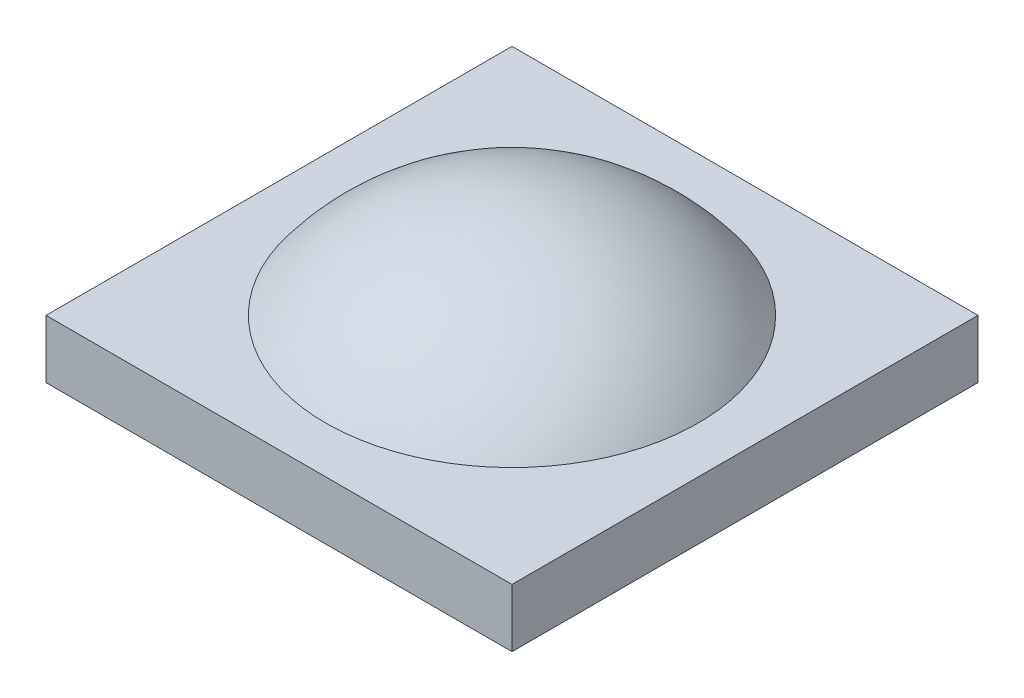
SolidWorks part; units mm, degrees
ref_plane "Front Plane" through (0, 0, 0) normal (0, 0, 1) x (1, 0, 0)
ref_plane "Top Plane" through (0, 0, 0) normal (0, 1, 0) x (1, 0, 0)
ref_plane "Right Plane" through (0, 0, 0) normal (1, 0, 0) x (0, 0, -1)
sketch "Sketch1" plane through (0, 0, 0) normal (0, 1, 0) x (1, 0, 0)
  line L1 (-25.4, -25.4) -> (25.4, -25.4)
  line L2 (-25.4, -25.4) -> (-25.4, 25.4)
  line L3 (-25.4, 25.4) -> (25.4, 25.4)
  line L4 (25.4, -25.4) -> (25.4, 25.4)
  line L5 (-25.4, -25.4) -> (25.4, 25.4) construction
  line L6 (-25.4, 25.4) -> (25.4, -25.4) construction
  point P0 (0, 0)
  dimension "D1" = 50.8
  dimension "D2" = 50.8
extrude "Boss-Extrude1" add sketch "Sketch1" along normal blind 6.35
sketch "Sketch2" plane through (0, 0, 0) normal (0, 0, 1) x (1, 0, 0)
  line L0 (0, 6.35) -> (-20.32, 6.35)
  line L1 (-25.4, 6.35) -> (25.4, 6.35) construction
  line L2 (0, 16.51) -> (0, 6.35)
  arc A0 (-20.32, 6.35) -> (0, 16.51) centre (0, -8.89) cw
  point P6 (0, 18.2671)
  point P7 (-0.3405, 5.1057)
  point P8 (0, 0)
  point P9 (0, 0)
  point P10 (0, 0)
  dimension "D1" = 25.4
  dimension "D2" = 10.16
revolve "Revolve1" add sketch "Sketch2" angle 360 about L2
